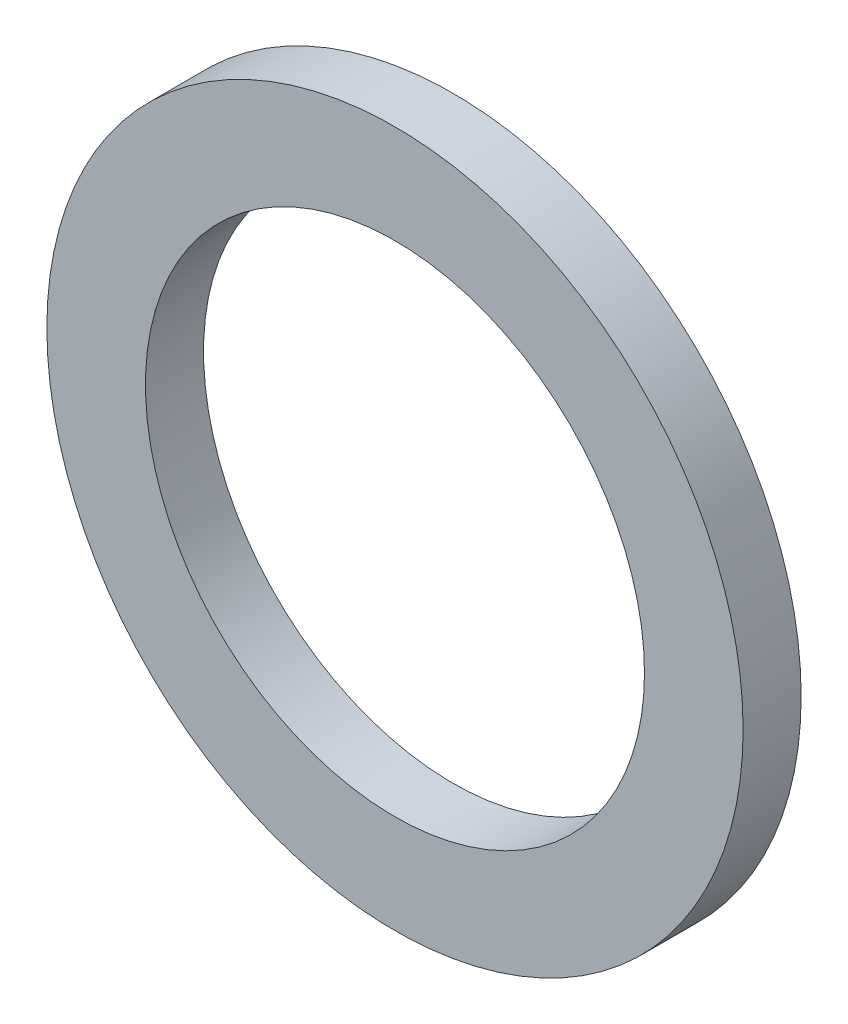
SolidWorks part; units mm, degrees
ref_plane "Front Plane" through (0, 0, 0) normal (0, 0, 1) x (1, 0, 0)
ref_plane "Top Plane" through (0, 0, 0) normal (0, 1, 0) x (1, 0, 0)
ref_plane "Right Plane" through (0, 0, 0) normal (1, 0, 0) x (0, 0, -1)
sketch "Sketch1" plane through (0, 0, 0) normal (0, 0, 1) x (1, 0, 0)
  circle A0 centre (0, 0) radius 6
extrude "Sleeve_Outer" add sketch "Sketch1" along normal blind 1 from offset 0
sketch "Sketch2" plane through (0, 0, 0) normal (0, 0, 1) x (1, 0, 0)
  circle A0 centre (0, 0) radius 4.3
extrude "Sleeve_Bore" cut sketch "Sketch2" along normal blind 1.2 from offset 0.1
